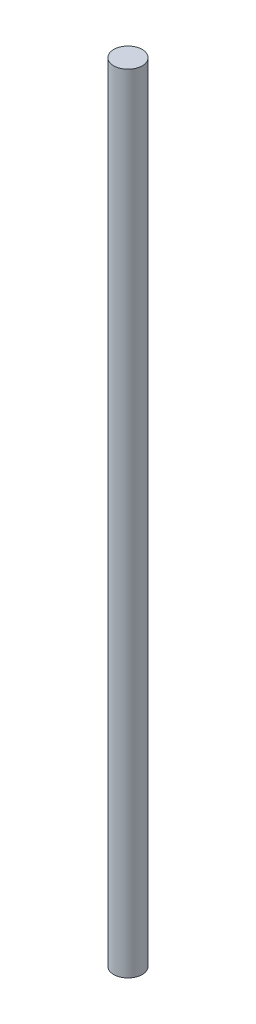
SolidWorks part; units mm, degrees
material "1060 Alloy"
ref_plane "Front Plane" through (0, 0, 0) normal (0, 0, 1) x (1, 0, 0)
ref_plane "Top Plane" through (0, 0, 0) normal (0, 1, 0) x (1, 0, 0)
ref_plane "Right Plane" through (0, 0, 0) normal (1, 0, 0) x (0, 0, -1)
sketch "Sketch1" plane through (0, 0, 0) normal (0, 1, 0) x (1, 0, 0)
  circle A0 centre (0, 0) radius 1.5
  dimension "D1" = 3
extrude "Boss-Extrude1" add sketch "Sketch1" along normal mid plane 83
